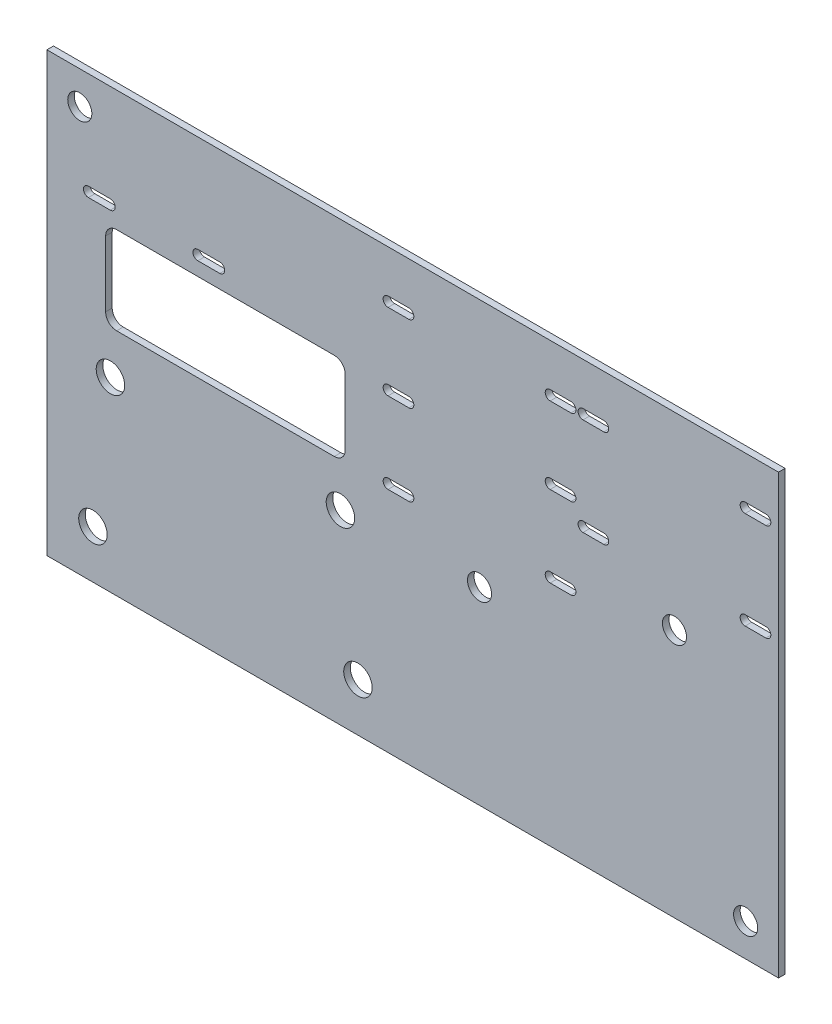
SolidWorks part; units mm, degrees
ref_plane "Piano frontale" through (0, 0, 0) normal (0, 0, 1) x (1, 0, 0)
ref_plane "Piano superiore" through (0, 0, 0) normal (0, 1, 0) x (1, 0, 0)
ref_plane "Piano destro" through (0, 0, 0) normal (1, 0, 0) x (0, 0, -1)
sketch "Schizzo1" plane through (0, 0, 0) normal (0, 0, 1) x (1, 0, 0)
  line L0 (-104, -103) -> (-148.5, -103) construction
  line L1 (31, -103) -> (-169, -103)
  line L2 (31, -103) -> (31, 97)
  line L3 (31, 97) -> (-169, 97)
  line L4 (-169, -103) -> (-169, 97)
  line L5 (31, -79) -> (13.5, -79) construction
  line L6 (13.5, -58) -> (13.5, -100) construction
  line L7 (-151.5, -77.0041) -> (-169, -77.0041) construction
  line L8 (-151.5, -100) -> (-151.5, -58) construction
  line L9 (-13.5, -11.5) -> (-19.5, -11.5) construction
  line L10 (-19.5, -24.5) -> (-13.5, -24.5) construction
  line L11 (-124.5, -24.5) -> (-118.5, -24.5) construction
  line L12 (-131.5, -87.5) -> (-127.5, -87.5) construction
  line L13 (-10.5, -87.5) -> (-6.5, -87.5) construction
  line L14 (-13.5, -11.5) -> (-19.5, -11.5)
  line L15 (-19.5, -24.5) -> (-13.5, -24.5)
  line L16 (-124.5, -24.5) -> (-118.5, -24.5)
  line L17 (-131.5, -87.5) -> (-127.5, -87.5)
  line L18 (-10.5, -87.5) -> (-6.5, -87.5)
  line L19 (-6.5, -70.5) -> (-10.5, -70.5)
  line L22 (-13.5, -18) -> (-19.5, -18)
  line L23 (-118.5, -18) -> (-124.5, -18)
  line L24 (-8.5, -70.5) -> (-8.5, -87.5)
  line L25 (-129.5, -87.5) -> (-129.5, -70.5)
  arc A3 (-13.5, -24.5) -> (-13.5, -11.5) centre (-13.5, -18) ccw construction
  arc A4 (-19.5, -11.5) -> (-19.5, -24.5) centre (-19.5, -18) ccw construction
  arc A5 (-118.5, -24.5) -> (-118.5, -11.5) centre (-118.5, -18) ccw construction
  arc A6 (-124.5, -11.5) -> (-124.5, -24.5) centre (-124.5, -18) ccw construction
  arc A7 (-127.5, -87.5) -> (-127.5, -70.5) centre (-127.5, -79) ccw construction
  arc A8 (-131.5, -70.5) -> (-131.5, -87.5) centre (-131.5, -79) ccw construction
  arc A9 (-6.5, -87.5) -> (-6.5, -70.5) centre (-6.5, -79) ccw construction
  arc A10 (-10.5, -70.5) -> (-10.5, -87.5) centre (-10.5, -79) ccw construction
  arc A14 (-13.5, -24.5) -> (-13.5, -11.5) centre (-13.5, -18) ccw
  arc A15 (-19.5, -11.5) -> (-19.5, -24.5) centre (-19.5, -18) ccw
  arc A16 (-118.5, -24.5) -> (-118.5, -11.5) centre (-118.5, -18) ccw
  arc A17 (-124.5, -11.5) -> (-124.5, -24.5) centre (-124.5, -18) ccw
  arc A18 (-127.5, -87.5) -> (-127.5, -70.5) centre (-127.5, -79) ccw
  arc A19 (-131.5, -70.5) -> (-131.5, -87.5) centre (-131.5, -79) ccw
  arc A20 (-6.5, -87.5) -> (-6.5, -70.5) centre (-6.5, -79) ccw
  arc A21 (-10.5, -70.5) -> (-10.5, -87.5) centre (-10.5, -79) ccw
  circle A22 centre (-121.5, -18) radius 6.5
  circle A24 centre (-16.5, -18) radius 6.5
  circle A26 centre (-129.5, -81) radius 6.5
  circle A27 centre (-8.5, -81) radius 6.5
  dimension "D2" = 13
  dimension "D3" = 13
  dimension "D1" = 200
extrude "Estrusione-Estrusione1" add sketch "Schizzo1" along normal blind 3
sketch "Schizzo5" plane through (31, 0, 0) normal (1, 0, 0) x (0, 0, -1)
  line L4 (0, -103) -> (0, 97)
  line L5 (0, 97) -> (-3, 97)
  line L6 (-3, 97) -> (-3, -103)
  line L7 (-3, -103) -> (0, -103)
  line L8 (0, -103) -> (0, 97)
  line L9 (0, 97) -> (-3, 97)
  line L10 (-3, 97) -> (-3, -103)
  line L11 (-3, -103) -> (0, -103)
  dimension "D1" = 0
extrude "Estrusione-Estrusione2" add sketch "Schizzo5" along normal blind 152.5
sketch "Schizzo7" plane through (-169, 0, 0) normal (-1, 0, 0) x (0, 0, 1)
  line L4 (0, 97) -> (0, -103)
  line L5 (0, -103) -> (3, -103)
  line L6 (3, -103) -> (3, 97)
  line L7 (3, 97) -> (0, 97)
  line L8 (0, 97) -> (0, -103)
  line L9 (0, -103) -> (3, -103)
  line L10 (3, -103) -> (3, 97)
  line L11 (3, 97) -> (0, 97)
  dimension "D1" = 0
extrude "Taglio-Estrusione3" cut sketch "Schizzo7" against normal blind 18.5
sketch "Schizzo10" plane through (0, 0, 0) normal (0, 0, -1) x (-1, 0, 0)
  line L0 (44.3051, 31.8) -> (93.6949, 31.8) construction
  line L1 (44.3051, 31.8) -> (93.6949, 31.8)
  line L2 (103.6949, 31.8) -> (103.6949, 1.8)
  line L3 (93.6949, 31.8) -> (44.3051, 31.8)
  line L4 (93.6949, 31.8) -> (93.6949, 11.8)
  line L5 (93.6949, 11.8) -> (44.3051, 11.8)
  line L6 (44.3051, 31.8) -> (44.3051, 11.8)
  line L7 (103.6949, 1.8) -> (34.3051, 1.8)
  line L8 (34.3051, 31.8) -> (34.3051, 1.8)
  line L9 (44.3051, 41.8) -> (93.6949, 41.8)
  line L10 (103.6949, 31.8) -> (103.6949, 41.8)
  line L11 (103.6949, 41.8) -> (93.6949, 41.8)
  line L12 (44.3051, 41.8) -> (34.3051, 41.8)
  line L13 (34.3051, 41.8) -> (34.3051, 31.8)
  line L15 (103.6949, 1.8) -> (118.6949, 1.8)
  line L16 (103.6949, 1.8) -> (103.6949, 41.8)
  line L17 (103.6949, 41.8) -> (118.6949, 41.8)
  line L18 (123.6949, 6.8) -> (123.6949, 36.8)
  line L19 (34.3051, 41.8) -> (19.3051, 41.8)
  line L20 (34.3051, 41.8) -> (34.3051, 1.8)
  line L21 (34.3051, 1.8) -> (19.3051, 1.8)
  line L22 (14.3051, 36.8) -> (14.3051, 6.8)
  arc A0 (118.6949, 1.8) -> (123.6949, 6.8) centre (118.6949, 6.8) ccw
  arc A1 (123.6949, 36.8) -> (118.6949, 41.8) centre (118.6949, 36.8) ccw
  arc A2 (14.3051, 6.8) -> (19.3051, 1.8) centre (19.3051, 6.8) ccw
  arc A3 (19.3051, 41.8) -> (14.3051, 36.8) centre (19.3051, 36.8) ccw
  dimension "D4" = 10
  dimension "D1" = 20
  dimension "D2" = 10
extrude "Taglio-Estrusione4" cut sketch "Schizzo10" against normal through all contours L12 L13 L8 L7 L2 L10 L11 L9 L6 L1 L4 L5 | L1 L6 L5 L4 | L16 L15 A0 L18 A1 L17 | L20 L19 A3 L22 A2 L21
sketch "Schizzo12" plane through (0, 0, 0) normal (0, 0, -1) x (-1, 0, 0)
  line L0 (-5.25, 3.3) -> (-14.75, 3.3) construction
  line L1 (-5.25, 1.05) -> (-14.75, 1.05)
  line L2 (-5.25, 5.55) -> (-14.75, 5.55)
  line L3 (-79.25, 3.3) -> (-88.75, 3.3) construction
  line L4 (-79.25, 1.05) -> (-88.75, 1.05)
  line L5 (-79.25, 5.55) -> (-88.75, 5.55)
  line L6 (-79.25, 40.3) -> (-88.75, 40.3) construction
  line L7 (-79.25, 38.05) -> (-88.75, 38.05)
  line L8 (-79.25, 42.55) -> (-88.75, 42.55)
  line L9 (-5.25, 40.3) -> (-14.75, 40.3) construction
  line L10 (-5.25, 38.05) -> (-14.75, 38.05)
  line L11 (-5.25, 42.55) -> (-14.75, 42.55)
  line L12 (-79.25, 40.3) -> (-88.75, 40.3) construction
  line L13 (-79.25, 38.05) -> (-88.75, 38.05)
  line L14 (-79.25, 42.55) -> (-88.75, 42.55)
  line L15 (-79.25, 75.3) -> (-88.75, 75.3) construction
  line L16 (-79.25, 73.05) -> (-88.75, 73.05)
  line L17 (-79.25, 77.55) -> (-88.75, 77.55)
  line L18 (-5.25, 75.3) -> (-14.75, 75.3) construction
  line L19 (-5.25, 73.05) -> (-14.75, 73.05)
  line L20 (-5.25, 77.55) -> (-14.75, 77.55)
  line L21 (-94.25, 30.8) -> (-103.75, 30.8) construction
  line L22 (-94.25, 28.55) -> (-103.75, 28.55)
  line L23 (-94.25, 33.05) -> (-103.75, 33.05)
  line L24 (-168.25, 30.8) -> (-177.75, 30.8) construction
  line L25 (-168.25, 28.55) -> (-177.75, 28.55)
  line L26 (-168.25, 33.05) -> (-177.75, 33.05)
  line L27 (-168.25, 75.3) -> (-177.75, 75.3) construction
  line L28 (-168.25, 73.05) -> (-177.75, 73.05)
  line L29 (-168.25, 77.55) -> (-177.75, 77.55)
  line L30 (-94.25, 75.3) -> (-103.75, 75.3) construction
  line L31 (-94.25, 73.05) -> (-103.75, 73.05)
  line L32 (-94.25, 77.55) -> (-103.75, 77.55)
  arc A0 (-5.25, 1.05) -> (-5.25, 5.55) centre (-5.25, 3.3) ccw
  circle A1 centre (-10, 75.3) radius 2.25
  circle A2 centre (-10, 75.3) radius 2.25
  circle A3 centre (-99, 75.3) radius 2.25
  circle A4 centre (-99, 75.3) radius 2.25
  circle A5 centre (-84, 75.3) radius 2.25
  circle A6 centre (-84, 75.3) radius 2.25
  circle A7 centre (-10, 3.3) radius 2.25
  circle A8 centre (-10, 3.3) radius 2.25
  circle A9 centre (-84, 3.3) radius 2.25
  circle A10 centre (-84, 3.3) radius 2.25
  circle A11 centre (-10, 40.3) radius 2.25
  circle A12 centre (-10, 40.3) radius 2.25
  circle A13 centre (-84, 40.3) radius 2.25
  circle A14 centre (-84, 40.3) radius 2.25
  circle A15 centre (-173, 75.3) radius 2.25
  circle A16 centre (-173, 75.3) radius 2.25
  circle A17 centre (-173, 30.8) radius 2.25
  circle A18 centre (-173, 30.8) radius 2.25
  circle A19 centre (-99, 30.8) radius 2.25
  circle A20 centre (-99, 30.8) radius 2.25
  arc A21 (-14.75, 5.55) -> (-14.75, 1.05) centre (-14.75, 3.3) ccw
  arc A22 (-79.25, 1.05) -> (-79.25, 5.55) centre (-79.25, 3.3) ccw
  arc A23 (-88.75, 5.55) -> (-88.75, 1.05) centre (-88.75, 3.3) ccw
  arc A24 (-79.25, 38.05) -> (-79.25, 42.55) centre (-79.25, 40.3) ccw
  arc A25 (-88.75, 42.55) -> (-88.75, 38.05) centre (-88.75, 40.3) ccw
  arc A26 (-5.25, 38.05) -> (-5.25, 42.55) centre (-5.25, 40.3) ccw
  arc A27 (-14.75, 42.55) -> (-14.75, 38.05) centre (-14.75, 40.3) ccw
  arc A28 (-79.25, 38.05) -> (-79.25, 42.55) centre (-79.25, 40.3) ccw
  arc A29 (-88.75, 42.55) -> (-88.75, 38.05) centre (-88.75, 40.3) ccw
  arc A30 (-79.25, 73.05) -> (-79.25, 77.55) centre (-79.25, 75.3) ccw
  arc A31 (-88.75, 77.55) -> (-88.75, 73.05) centre (-88.75, 75.3) ccw
  arc A32 (-5.25, 73.05) -> (-5.25, 77.55) centre (-5.25, 75.3) ccw
  arc A33 (-14.75, 77.55) -> (-14.75, 73.05) centre (-14.75, 75.3) ccw
  arc A34 (-94.25, 28.55) -> (-94.25, 33.05) centre (-94.25, 30.8) ccw
  arc A35 (-103.75, 33.05) -> (-103.75, 28.55) centre (-103.75, 30.8) ccw
  arc A36 (-168.25, 28.55) -> (-168.25, 33.05) centre (-168.25, 30.8) ccw
  arc A37 (-177.75, 33.05) -> (-177.75, 28.55) centre (-177.75, 30.8) ccw
  arc A38 (-168.25, 73.05) -> (-168.25, 77.55) centre (-168.25, 75.3) ccw
  arc A39 (-177.75, 77.55) -> (-177.75, 73.05) centre (-177.75, 75.3) ccw
  arc A40 (-94.25, 73.05) -> (-94.25, 77.55) centre (-94.25, 75.3) ccw
  arc A41 (-103.75, 77.55) -> (-103.75, 73.05) centre (-103.75, 75.3) ccw
  point P32 (-10, 3.3)
  point P42 (-84, 3.3)
  point P49 (-84, 40.3)
  point P56 (-10, 40.3)
  point P62 (-84, 40.3)
  point P69 (-84, 75.3)
  point P76 (-10, 75.3)
  point P81 (-99, 30.8)
  point P90 (-173, 30.8)
  point P97 (-173, 75.3)
  point P104 (-99, 75.3)
  dimension "D11" = 2
  dimension "D1" = 0
  dimension "D2" = 0
  dimension "D3" = 0
  dimension "D4" = 0
  dimension "D5" = 0
  dimension "D6" = 0
  dimension "D7" = 0
  dimension "D8" = 0
  dimension "D9" = 0
  dimension "D10" = 0
  dimension "D12" = 2
  dimension "D13" = 2
  dimension "D14" = 2
  dimension "D15" = 2
  dimension "D16" = 2
extrude "Taglio-Estrusione5" cut sketch "Schizzo12" against normal through all contours A8 L1 A0 L2 | L2 A21 L1 A8 | A8 | L10 A26 L11 A12 | A12 | L11 A27 L10 A12 | L19 A32 L20 A2 | A2 | L20 A33 L19 A2 | L17 A31 L16 A6 | A6 | L16 A30 L17 A6 | L31 A40 L32 A4 | A4 | L32 A41 L31 A4 | L7 A24 L8 A14 | A14 | L14 A25 L13 A14 | A10 | L4 A22 L5 A10 | L5 A23 L4 A10 | L22 A34 L23 A20 | A20 | L23 A35 L22 A20 | L25 A36 L26 A18 | A18 | L26 A37 L25 A18 | L28 A38 L29 A16 | A16 | L29 A39 L28 A16
sketch "Schizzo13" plane through (0, 0, 0) normal (0, 0, -1) x (-1, 0, 0)
  line L0 (131.5857, 50.3) -> (121.5857, 50.3) construction
  line L1 (131.5857, 48.05) -> (121.5857, 48.05)
  line L2 (131.5857, 52.55) -> (121.5857, 52.55)
  line L3 (81.5857, 50.3) -> (71.5857, 50.3) construction
  line L4 (81.5857, 48.05) -> (71.5857, 48.05)
  line L5 (81.5857, 52.55) -> (71.5857, 52.55)
  circle A1 centre (126.5857, 50.3) radius 2.25
  circle A2 centre (126.5857, 50.3) radius 2.25
  circle A3 centre (76.5857, 50.3) radius 2.25
  circle A4 centre (76.5857, 50.3) radius 2.25
  arc A6 (131.5857, 48.05) -> (131.5857, 52.55) centre (131.5857, 50.3) ccw
  arc A7 (121.5857, 52.55) -> (121.5857, 48.05) centre (121.5857, 50.3) ccw
  arc A8 (81.5857, 48.05) -> (81.5857, 52.55) centre (81.5857, 50.3) ccw
  arc A9 (71.5857, 52.55) -> (71.5857, 48.05) centre (71.5857, 50.3) ccw
  point P8 (126.5857, 50.3)
  point P15 (76.5857, 50.3)
  dimension "D3" = 10
  dimension "D4" = 4.5
  dimension "D1" = 0
  dimension "D2" = 0
extrude "Taglio-Estrusione6" cut sketch "Schizzo13" against normal through all contours L1 A6 L2 A2 | A2 | L2 A7 L1 A2 | L4 A8 L5 A4 | A4 | L5 A9 L4 A4
sketch "Schizzo14" plane through (0, 0, 0) normal (0, 0, -1) x (-1, 0, 0)
  line L0 (-183.5, -103) -> (-183.5, -88) construction
  line L1 (-183.5, -103) -> (-183.5, 97) construction
  line L2 (-183.5, -88) -> (-168.5, -88) construction
  line L3 (150.5, 97) -> (150.5, 82) construction
  line L4 (150.5, 97) -> (150.5, -103) construction
  line L5 (150.5, 82) -> (135.5, 82) construction
  line L6 (-17, 3.3) -> (-77, 3.3) construction
  line L7 (-47, 3.3) -> (-47, -16.7) construction
  line L8 (-106, 30.8) -> (-166, 30.8) construction
  line L9 (-136, 30.8) -> (-136, 10.8) construction
  circle A0 centre (-168.5, -88) radius 5.5
  circle A1 centre (135.5, 82) radius 5.5
  arc A2 (-14.75, 5.55) -> (-14.75, 1.05) centre (-14.75, 3.3) ccw construction
  arc A3 (-79.25, 1.05) -> (-79.25, 5.55) centre (-79.25, 3.3) ccw construction
  circle A4 centre (-47, -16.7) radius 5.5
  circle A5 centre (-136, 10.8) radius 5.5
  arc A6 (-103.75, 33.05) -> (-103.75, 28.55) centre (-103.75, 30.8) ccw construction
  arc A7 (-168.25, 28.55) -> (-168.25, 33.05) centre (-168.25, 30.8) ccw construction
  point P30 (0, 0)
  point P34 (-106, 30.8)
  point P35 (0, 0)
  dimension "D3" = 11
  dimension "D1" = 15
  dimension "D2" = 15
  dimension "D4" = 20
  dimension "D5" = 20
extrude "Taglio-Estrusione7" cut sketch "Schizzo14" against normal through all
